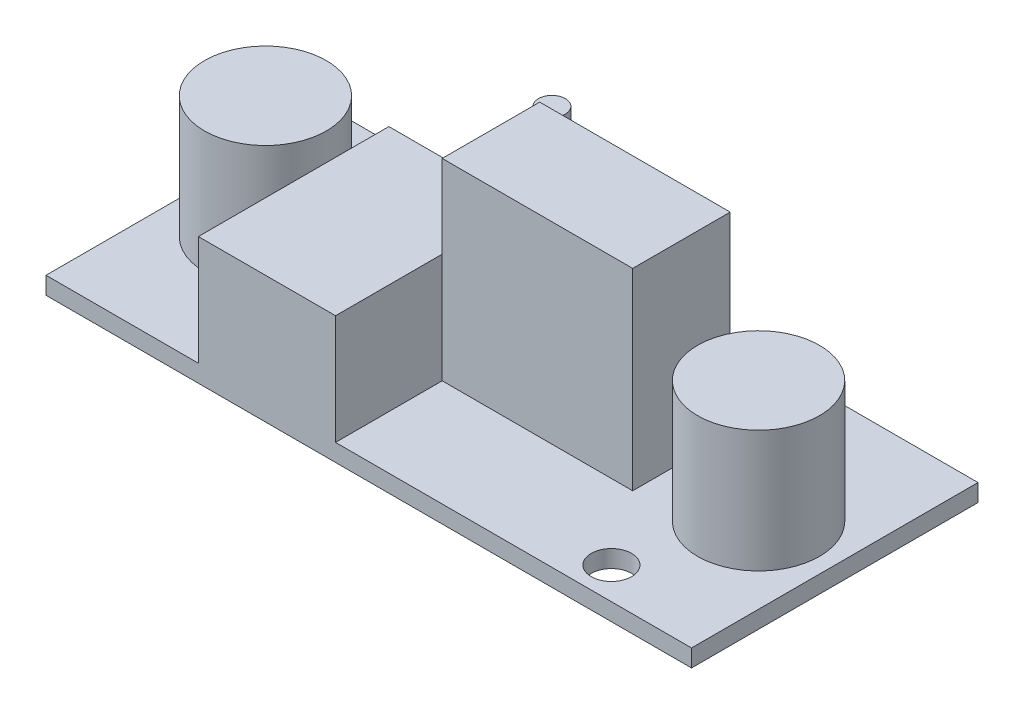
SolidWorks part; units mm, degrees
ref_plane "Front Plane" through (0, 0, 0) normal (0, 0, 1) x (1, 0, 0)
ref_plane "Top Plane" through (0, 0, 0) normal (0, 1, 0) x (1, 0, 0)
ref_plane "Right Plane" through (0, 0, 0) normal (1, 0, 0) x (0, 0, -1)
sketch "Sketch1" plane through (0, 0, 0) normal (0, 1, 0) x (1, 0, 0)
  line L1 (-26.8986, -11.938) -> (26.8986, -11.938)
  line L2 (-26.8986, -11.938) -> (-26.8986, 11.938)
  line L3 (-26.8986, 11.938) -> (26.8986, 11.938)
  line L4 (26.8986, -11.938) -> (26.8986, 11.938)
  line L5 (-26.8986, -11.938) -> (26.8986, 11.938) construction
  line L6 (-26.8986, 11.938) -> (26.8986, -11.938) construction
  point P0 (0, 0)
extrude "Boss-Extrude1" add sketch "Sketch1" along normal blind 1.4478 contours L2 L1 L4 L3
sketch "Sketch2" plane through (0, 1.4478, 0) normal (0, 1, 0) x (1, 0, 0)
  line L0 (26.8986, -11.938) -> (17.5768, -11.938)
  line L1 (-26.8986, -11.938) -> (26.8986, -11.938) construction
  circle A0 centre (17.5768, -9.29) radius 1.6827
  circle A3 centre (-17.5768, 9.2901) radius 1.6827
extrude "Cut-Extrude1" cut sketch "Sketch2" against normal through all contours A3 | A0
sketch "Sketch3" plane through (0, 1.4478, 0) normal (0, 1, 0) x (1, 0, 0)
  circle A0 centre (-20.5486, 0) radius 5.08
  circle A1 centre (20.5486, 0) radius 5.08
extrude "Boss-Extrude2" add sketch "Sketch3" along normal blind 10.16 contours A1 | A0
sketch "Sketch4" plane through (0, 1.4478, 0) normal (0, 1, 0) x (1, 0, 0)
  line L0 (-26.8986, -11.938) -> (-14.1986, -11.938)
  line L1 (-26.8986, -11.938) -> (26.8986, -11.938) construction
  line L3 (-14.1986, -11.938) -> (-2.7686, -11.938)
  line L4 (-14.1986, -11.938) -> (-14.1986, 3.937)
  line L5 (-14.1986, 3.937) -> (-2.7686, 3.937)
  line L6 (-2.7686, -11.938) -> (-2.7686, 3.937)
extrude "Boss-Extrude3" add sketch "Sketch4" along normal blind 9.144 contours L4 L3 L6 L5
sketch "Sketch5" plane through (0, 1.4478, 0) normal (0, 1, 0) x (1, 0, 0)
  line L0 (-26.8986, 11.938) -> (-8.6106, 11.938)
  line L1 (-26.8986, 11.938) -> (26.8986, 11.938) construction
  line L3 (-8.6106, 11.938) -> (0.8636, 11.938)
  line L4 (-8.6106, 11.938) -> (-8.6106, 7.7216)
  line L5 (-8.6106, 7.7216) -> (0.8636, 7.7216)
  line L6 (0.8636, 11.938) -> (0.8636, 7.7216)
extrude "Boss-Extrude4" add sketch "Sketch5" along normal blind 9.144 contours L4 L3 L6 L5
sketch "Sketch6" plane through (0, 10.5918, 0) normal (0, 1, 0) x (1, 0, 0)
  circle A0 centre (-7.3406, 10.668) radius 1.1176
extrude "Boss-Extrude5" add sketch "Sketch6" along normal blind 1.524 contours A0
sketch "Sketch7" plane through (0, 1.4478, 0) normal (0, 1, 0) x (1, 0, 0)
  line L0 (-2.7686, -11.938) -> (-2.7686, -3.048)
  line L1 (-2.7686, -11.938) -> (-2.7686, 3.937) construction
  line L3 (-2.7686, -3.048) -> (13.1064, -3.048)
  line L4 (-2.7686, -3.048) -> (-2.7686, 5.08)
  line L5 (-2.7686, 5.08) -> (13.1064, 5.08)
  line L6 (13.1064, -3.048) -> (13.1064, 5.08)
extrude "Boss-Extrude6" add sketch "Sketch7" along normal blind 16.0528 contours L4 L3 L6 L5
